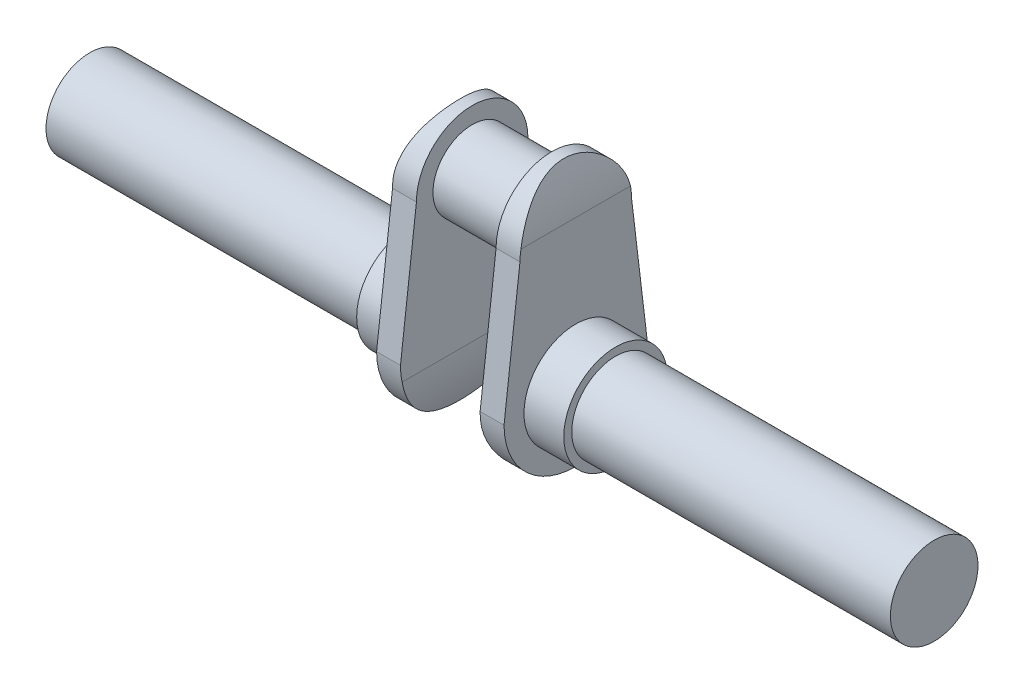
SolidWorks part; units mm, degrees
ref_plane "Front Plane" through (0, 0, 0) normal (0, 0, 1) x (1, 0, 0)
ref_plane "Top Plane" through (0, 0, 0) normal (0, 1, 0) x (1, 0, 0)
ref_plane "Right Plane" through (0, 0, 0) normal (1, 0, 0) x (0, 0, -1)
sketch "Sketch1" plane through (0, 0, 0) normal (1, 0, 0) x (0, 0, -1)
  line L0 (-22.225, 53.1813) -> (-28.575, 0)
  line L1 (22.225, 53.1813) -> (28.575, 0)
  arc A0 (-27.7717, 6.728) -> (27.7717, 6.728) centre (0, 0) ccw
  arc A1 (22.225, 53.1813) -> (-22.225, 53.1813) centre (0, 53.1813) ccw
  circle A3 centre (0, 0) radius 20.6375
  dimension "D2" = 44.45
  dimension "D3" = 57.15
  dimension "D4" = 41.275
  dimension "D1" = 53.1813
extrude "Boss-Extrude1" add sketch "Sketch1" along normal blind 9.525 contours L1 A1 L0 A0 A3 | A3
sketch "Sketch2" plane through (0, 0, 0) normal (-1, 0, 0) x (0, 0, 1)
  circle A0 centre (0, 0) radius 20.6375
  dimension "D1" = 41.275
extrude "Boss-Extrude3" add sketch "Sketch2" along normal blind 15.875
sketch "Sketch3" plane through (9.525, 0, 0) normal (1, 0, 0) x (0, 0, -1)
  circle A0 centre (0, 53.1813) radius 15.6312
  arc A1 (22.225, 53.1813) -> (-22.225, 53.1813) centre (0, 53.1813) ccw construction
extrude "Boss-Extrude4" add sketch "Sketch3" along normal blind 15.875
sketch "Sketch4" plane through (0, 0, 0) normal (0, 0, 1) x (1, 0, 0)
  line L0 (9.525, 75.4063) -> (0, 75.4063) construction
  line L2 (4.7625, 75.4063) -> (-6.1781, 75.4063)
  line L3 (-6.1781, 75.4063) -> (-6.1781, 53.1813)
  line L4 (-6.1781, 53.1813) -> (0, 53.1813)
  arc A0 (4.7625, 75.4063) -> (0, 53.1813) centre (44.4, 55.2897) ccw
  point P3 (0, 0)
  dimension "D1" = 44.45
extrude "Cut-Extrude1" cut sketch "Sketch4" against normal through all both and the other way through all
sketch "Sketch5" plane through (0, 0, 0) normal (0, 0, 1) x (1, 0, 0)
  line L0 (0, -28.575) -> (9.525, -28.575) construction
  line L1 (4.7625, -28.575) -> (17.4625, -28.575)
  line L2 (17.4625, -28.575) -> (17.4625, 0)
  line L3 (17.4625, 0) -> (9.525, 0)
  arc A0 (4.7625, -28.575) -> (9.525, 0) centre (-60.2582, -3.0538) ccw
  dimension "D1" = 69.85
  dimension "D2" = 12.7
extrude "Cut-Extrude2" cut sketch "Sketch5" against normal through all both and the other way through all
mirror "Mirror1" about plane through (25.4, 53.1813, 0) normal (1, 0, 0) of bodies 106
sketch "Sketch6" plane through (-15.875, 0, 0) normal (-1, 0, 0) x (0, 0, 1)
  circle A0 centre (0, 0) radius 20.6375 construction
  circle A1 centre (0, 0) radius 20.6375
  circle A2 centre (0, 0) radius 17.4625
  dimension "D1" = 3.175
extrude "Boss-Extrude5" add sketch "Sketch6" along normal blind 127 contours A2
sketch "Sketch7" plane through (66.675, 0, 0) normal (1, 0, 0) x (0, 0, -1)
  circle A1 centre (0, 0) radius 20.6375
  circle A2 centre (0, 0) radius 20.6375
  circle A3 centre (0, 0) radius 17.4625
  dimension "D1" = 0
  dimension "D2" = 3.175
extrude "Boss-Extrude6" add sketch "Sketch7" along normal blind 127 contours A3
